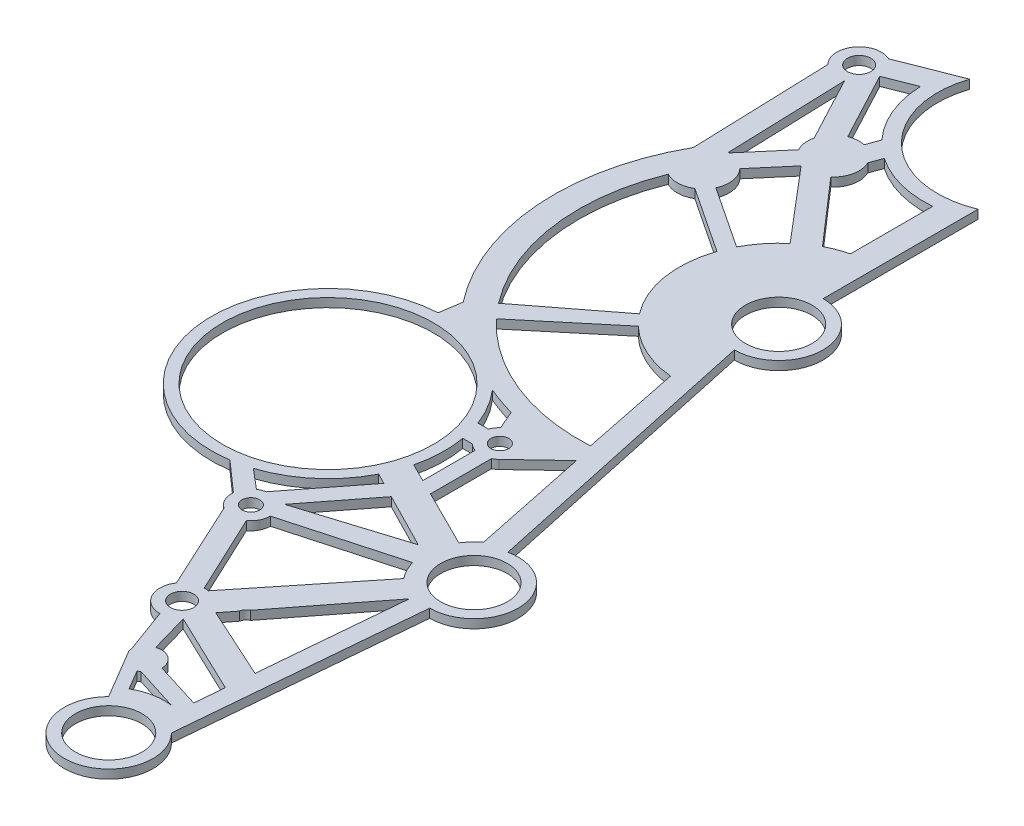
SolidWorks part; units mm, degrees
ref_plane "Front" through (0, 0, 0) normal (0, 0, 1) x (1, 0, 0)
ref_plane "Top" through (0, 0, 0) normal (0, 1, 0) x (1, 0, 0)
ref_plane "Right" through (0, 0, 0) normal (1, 0, 0) x (0, 0, -1)
sketch "Sketch1" plane through (0, 0, 0) normal (0, 1, 0) x (1, 0, 0)
  line L0 (15.9743, 29.6759) -> (13.4124, 22.7054)
  line L1 (59.4628, -19.5789) -> (55.6662, -62.316)
  line L2 (44.3338, -62.316) -> (13.4124, -10.0901)
  line L3 (46.6071, 96.669) -> (46.6071, 64.169)
  line L4 (46.6071, 48.169) -> (57.7856, -3.8043)
  circle A1 centre (46.6071, 56.169) radius 6
  circle A2 centre (59.4628, -11.6024) radius 6
  circle A3 centre (50, -67.9636) radius 6
  circle A4 centre (46.6071, 56.169) radius 40.5
  circle A5 centre (15.2468, 6.3076) radius 16.5
  circle A6 centre (16.9224, -4.8813) radius 1.65
  circle A7 centre (26.4357, 7.9833) radius 1.65
  circle A8 centre (13.5711, 17.4966) radius 2
  circle A9 centre (4.0578, 4.632) radius 2
  circle A10 centre (44.3338, -37.4884) radius 1.6
  circle A11 centre (59.4628, -11.6024) radius 7.9765
  circle A12 centre (50, -67.9636) radius 8
  circle A13 centre (46.6071, 56.169) radius 8
  circle A14 centre (27.2332, -19.5789) radius 1.6
  circle A15 centre (40.0896, 12.4397) radius 1.6
  dimension "D1" = 82
  dimension "D2" = 12
  dimension "D3" = 12
  dimension "D4" = 12
  dimension "D6" = 57.15
  dimension "D7" = 33
  dimension "D9" = 81
  dimension "D5" = 68.98
extrude "Boss-Extrude2" add sketch "Sketch1" along normal blind 1.5875
sketch "Sketch2" plane through (0, 1.5875, 0) normal (0, 1, 0) x (1, 0, 0)
  circle A0 centre (40.5463, 106.6726) radius 16.1315
sketch "Sketch3" plane through (0, 1.5875, 0) normal (0, 1, 0) x (1, 0, 0)
  line L0 (13.4124, 22.7054) -> (25.5511, 101.703)
  line L1 (46.6071, 64.169) -> (46.6071, 92.0844)
  line L2 (46.6071, 96.669) -> (46.6071, 64.169) construction
  line L3 (46.6071, 64.169) -> (36.5959, 64.169)
  line L4 (36.5959, 64.169) -> (13.4124, 22.7054)
  circle A0 centre (40.5463, 106.6726) radius 15.7972
  line M1 (15.9743, 29.6759) -> (13.4124, 22.7054)
  line M9 (46.6071, 64.169) -> (46.6071, 96.669)
  arc M10 (46.6071, 96.669) -> (15.9743, 29.6759) centre (46.6071, 56.169) ccw
extrude "Boss-Extrude3" add sketch "Sketch3" against normal blind 1.5875 contours A0 M9 M10 | A0 L0 M10 | L0 M1 M10
sketch "Sketch4" plane through (0, 1.5875, 0) normal (0, 1, 0) x (1, 0, 0)
  circle A4 centre (40.5463, 106.6726) radius 4.4
  circle A6 centre (40.5463, 117.1402) radius 2.1
  circle A7 centre (30.0786, 106.6726) radius 2.1
  circle A8 centre (51.0139, 106.6726) radius 2.1
  circle A9 centre (40.5463, 96.205) radius 2.1
extrude "Cut-Extrude1" cut sketch "Sketch4" against normal blind 1.5875
sketch "Sketch5" plane through (0, 1.5875, 0) normal (0, 1, 0) x (1, 0, 0)
  line L8 (25.5464, 111.6279) -> (15.0699, 107.5194)
  line L9 (15.0699, 107.5194) -> (10.4945, 101.1182)
  line L10 (10.4945, 101.1182) -> (11.3241, 76.0526)
  line L11 (11.3241, 76.0526) -> (25.5464, 90.3595)
  line L12 (25.5464, 111.6279) -> (28.4516, 99.4256)
  line L13 (28.4516, 99.4256) -> (25.5464, 90.3595)
  circle A3 centre (13.3703, 103.8984) radius 4
  arc A4 (46.6071, 92.0844) -> (25.5511, 101.703) centre (40.5463, 106.6726) ccw construction
  arc A5 (23.685, 89.558) -> (14.718, 31.2023) centre (46.6071, 56.169) ccw construction
  arc M7 (46.6071, 92.0844) -> (25.5511, 101.703) centre (40.5463, 106.6726) ccw
  line M8 (25.5511, 101.703) -> (23.685, 89.558)
  arc M9 (23.685, 89.558) -> (14.718, 31.2023) centre (46.6071, 56.169) ccw
extrude "Boss-Extrude4" add sketch "Sketch5" against normal blind 1.5875 contours A3 L10 L8 M9 M8 M7 | L9 A3 | L9 A3
sketch "Sketch7" plane through (0, 1.5875, 0) normal (0, 1, 0) x (1, 0, 0)
  circle A0 centre (13.3703, 103.8984) radius 2.1
extrude "Cut-Extrude2" cut sketch "Sketch7" against normal blind 1.5875
sketch "Sketch8" plane through (0, 1.5875, 0) normal (0, 1, 0) x (1, 0, 0)
  line L0 (16.7927, 103.8984) -> (22.2708, 106.0467)
  line L1 (14.5115, 100.6719) -> (15.4014, 73.7824)
  line L2 (19.6339, 71.8168) -> (30.738, 64.4472)
  line L3 (14.2729, 100.5972) -> (23.3039, 83.6092)
  line L4 (10.4945, 101.1182) -> (11.3241, 76.0526) construction
  line L5 (25.5464, 111.6279) -> (15.0699, 107.5194) construction
  line L6 (16.7449, 104.4686) -> (26.5345, 86.0537)
  line L7 (27.1349, 94.2421) -> (23.3039, 83.6092)
  line L8 (23.3039, 83.6092) -> (35.0212, 69.8118)
  line L9 (17.8533, 69.8118) -> (29.6736, 61.9669)
  line L11 (18.0815, 34.2079) -> (32.4247, 45.2504)
  circle A0 centre (44.3338, -37.4884) radius 3.5
  circle A1 centre (27.2332, -19.5789) radius 3.5
  circle A2 centre (40.0896, 12.4397) radius 3.5
  circle A3 centre (46.6071, 56.169) radius 17.8985
  circle A4 centre (46.6071, 56.169) radius 36
  circle A5 centre (40.5463, 106.6726) radius 18.2861
  circle A6 centre (13.3703, 103.8984) radius 3.4224
  circle A7 centre (15.4014, 73.7824) radius 4.6667
  dimension "D1" = 4
  dimension "D3" = 4
  dimension "D4" = 0.25
  dimension "D5" = 0
  dimension "D2" = 4
extrude "Cut-Extrude3" cut sketch "Sketch8" against normal blind 1.5875
sketch "Sketch9" plane through (0, 1.5875, 0) normal (0, 1, 0) x (1, 0, 0)
  line L0 (30.2325, 91.5726) -> (29.4295, 89.401)
  line L1 (38.418, 72.2514) -> (28.3091, 83.855)
  line L2 (42.0745, 88.4505) -> (42.0745, 73.6378)
  circle A0 centre (25.2577, 87.3576) radius 4.6453
  circle A1 centre (17.1296, 32.1928) radius 4.6169
  circle A2 centre (40.5463, 106.6726) radius 18.2861
  circle A3 centre (46.6071, 56.169) radius 18.0472
extrude "Cut-Extrude4" cut sketch "Sketch9" against normal blind 1.5875 contours A3 L2 A2 L0 A0 L1
sketch "Sketch10" plane through (0, 1.5875, 0) normal (0, 1, 0) x (1, 0, 0)
  line L0 (15.4014, 78.4492) -> (21.149, 85.19)
  line L2 (18.8226, 76.9563) -> (23.9027, 82.9142)
  line L4 (15.4014, 78.4492) -> (18.8226, 76.9563)
  circle A0 centre (25.2577, 87.3576) radius 4.6453
  arc A3 (19.6339, 71.8168) -> (15.247, 78.4466) centre (15.4014, 73.7824) ccw construction
  dimension "D1" = 360
extrude "Boss-Extrude5" add sketch "Sketch10" against normal blind 1.5875 contours A0 L0 L4 L2 | A0
sketch "Sketch11" plane through (0, 1.5875, 0) normal (0, 1, 0) x (1, 0, 0)
  line L0 (34.2476, 43.223) -> (20.3075, 31.5858)
  line L1 (18.0815, 34.2079) -> (32.4247, 45.2504)
  line L2 (44.9381, 38.3485) -> (48.6267, 20.2257)
  line L3 (20.3075, 31.5858) -> (18.9387, 22.3893)
  line L4 (48.6267, 20.2257) -> (42.6756, 14.7982)
  line L5 (42.4947, 9.8969) -> (49.6526, 16.6671)
  line L6 (49.6526, 16.6671) -> (54.0294, -4.4505)
  line L7 (36.8042, 13.6463) -> (30.0249, 13.6463)
  line L8 (37.6846, 9.8969) -> (31.3516, 9.8969)
  line L9 (31.4919, 3.419) -> (51.8937, -6.767)
  line L10 (29.9364, -1.2067) -> (50.4818, -11.7165)
  line L11 (13.4124, -10.0901) -> (23.7488, -19.2488)
  line L12 (17.4775, -10.0409) -> (25.311, -16.654)
  line L13 (29.2749, -16.7361) -> (48.5367, -10.7215)
  line L14 (30.7332, -19.5789) -> (50.8084, -14.0052)
  line L15 (25.311, -22.5038) -> (32.7084, -38.4713)
  line L16 (29.2749, -22.4218) -> (36, -36.7441)
  line L17 (56.1688, -19.9584) -> (52.7614, -58.3107)
  line L18 (36, -44.7441) -> (38.9873, -52.934)
  line L19 (38.9293, -43.468) -> (40.9076, -50.4068)
  line L20 (36.8042, -36.8258) -> (52.5095, -17.2877)
  line L21 (56.1688, -19.9584) -> (40, -40.7441)
  line L22 (40.9076, -39.5774) -> (53.8998, -45.4974)
  line L23 (44.682, -53.0586) -> (52.9986, -55.6414)
  line L24 (43.3802, -55.4958) -> (51.3, -58.008)
  line L25 (38.9293, -43.468) -> (53.4636, -50.4068)
  line L26 (38.9883, -53.2874) -> (33.3197, -43.7134)
  line L27 (13.4124, -10.0901) -> (32.1078, -41.6663)
  line L29 (40.3027, -55.5075) -> (43.2676, -60.5152)
  line L30 (44.3338, -62.316) -> (13.4124, -10.0901) construction
  line L31 (42.8898, -55.7493) -> (44.9751, -59.2714)
  line L32 (36.2603, 18.3036) -> (37.6846, 14.9825)
  line L33 (40.0896, 17.4602) -> (40.9076, 15.8428)
  line L34 (38.9293, 9.1377) -> (38.9293, -0.2943)
  line L35 (41.6928, 9.3285) -> (41.6928, -1.674)
  line L36 (38.9293, -0.2943) -> (26.5747, -16.1414)
  line L37 (41.6928, -1.674) -> (30.1797, -16.4535)
  circle A0 centre (46.6071, 56.169) radius 17.8985
  circle A1 centre (40.0896, 12.4397) radius 3.5
  circle A2 centre (46.6071, 56.169) radius 36
  circle A3 centre (15.2468, 6.3076) radius 16.5
  circle A4 centre (46.6071, 56.169) radius 39.2536
  circle A5 centre (59.4628, -11.6024) radius 8.9818
  circle A6 centre (27.2332, -19.5789) radius 3.5
  circle A8 centre (50, -67.9636) radius 10.0401
  circle A9 centre (41.8323, -53.1027) radius 2.8501
  circle A13 centre (36, -40.7441) radius 2.1
  circle A14 centre (36, -40.7441) radius 4
extrude "Cut-Extrude5" cut sketch "Sketch11" against normal blind 1.5875
sketch "Sketch13" plane through (0, 1.5875, 0) normal (0, 1, 0) x (1, 0, 0)
  line L4 (14.6824, -12.2352) -> (24.5373, -21.0241)
  line L5 (44.3338, -62.316) -> (38.9883, -53.2874) construction
  line L6 (24.5373, -21.0241) -> (36.3122, -48.7676)
  line L7 (36.3122, -48.7676) -> (14.6824, -12.2352)
  circle A0 centre (27.2332, -19.5789) radius 3.5
extrude "Cut-Extrude9" cut sketch "Sketch13" against normal blind 1.5875 contours A0 L4 L7 L6
sketch "Sketch19" plane through (0, 1.5875, 0) normal (0, 1, 0) x (1, 0, 0)
  circle A0 centre (36, -40.7441) radius 4
extrude "Boss-Extrude8" add sketch "Sketch19" against normal blind 1.5875
sketch "Sketch20" plane through (0, 1.5875, 0) normal (0, 1, 0) x (1, 0, 0)
  circle A0 centre (36, -40.7441) radius 2.1
extrude "Cut-Extrude12" cut sketch "Sketch20" against normal blind 1.5875
sketch "Sketch21" plane through (0, 1.5875, 0) normal (0, 1, 0) x (1, 0, 0)
  circle A0 centre (40.5463, 106.6726) radius 15.7972
extrude "Cut-Extrude13" cut sketch "Sketch21" against normal blind 10
sketch "Sketch22" plane through (0, 1.5875, 0) normal (0, 1, 0) x (1, 0, 0)
  circle A0 centre (15.2468, 6.3076) radius 21
  circle A1 centre (19.711, 27.578) radius 1.9621
extrude "Boss-Extrude9" add sketch "Sketch22" against normal blind 1.5875 contours A1 A0 | A0 A1 | A0 A1
sketch "Sketch23" plane through (0, 1.5875, 0) normal (0, 1, 0) x (1, 0, 0)
  circle A0 centre (15.2468, 6.3076) radius 19
extrude "Cut-Extrude15" cut sketch "Sketch23" against normal blind 1.5875
